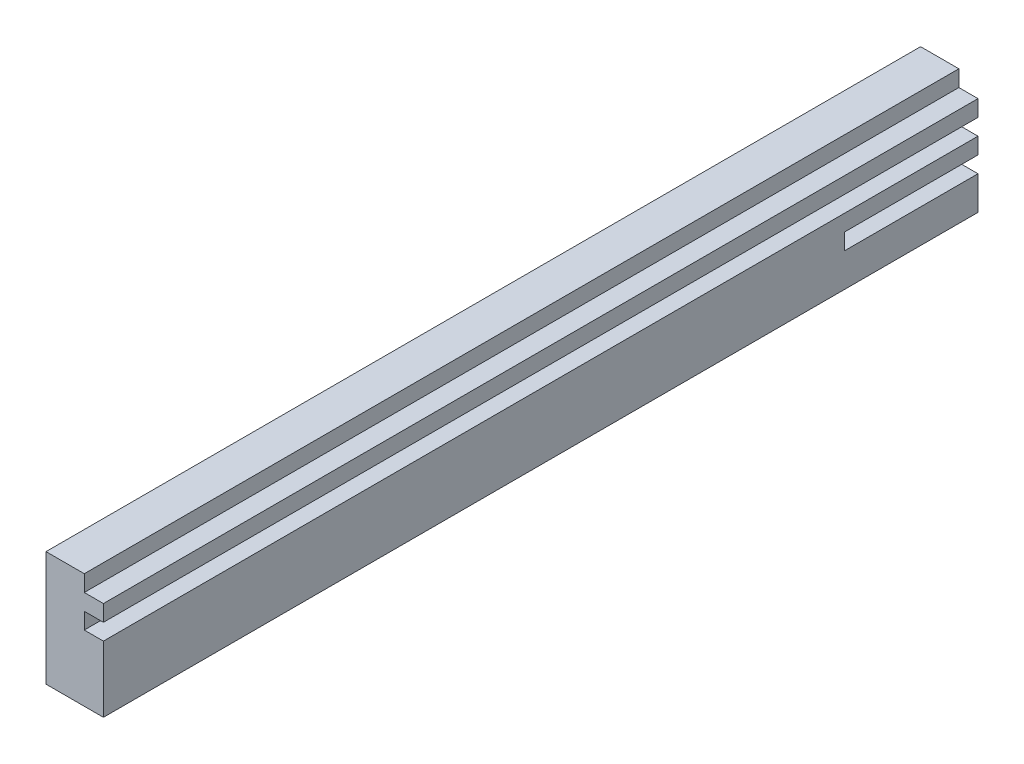
SolidWorks part; units mm, degrees
ref_plane "Front Plane" through (0, 0, 0) normal (0, 0, 1) x (1, 0, 0)
ref_plane "Top Plane" through (0, 0, 0) normal (0, 1, 0) x (1, 0, 0)
ref_plane "Right Plane" through (0, 0, 0) normal (1, 0, 0) x (0, 0, -1)
sketch "Sketch1" plane through (0, 0, 0) normal (1, 0, 0) x (0, 0, -1)
  line L1 (0, 0) -> (457, 0)
  line L2 (0, 0) -> (0, 60)
  line L3 (0, 60) -> (457, 60)
  line L4 (457, 0) -> (457, 60)
  dimension "D1" = 60
  dimension "D2" = 457
extrude "Boss-Extrude1" add sketch "Sketch1" along normal blind 30
sketch "Sketch2" plane through (30, 0, 0) normal (1, 0, 0) x (0, 0, -1)
  line L0 (457, 0) -> (457, 60) construction
  line L1 (0, 60) -> (457, 60)
  line L2 (0, 60) -> (0, 51.5)
  line L3 (0, 51.5) -> (457, 51.5)
  line L4 (457, 60) -> (457, 51.5)
  line L5 (0, 60) -> (0, 0) construction
  line L6 (0, 43) -> (457, 43)
  line L7 (0, 43) -> (0, 34.5)
  line L8 (0, 34.5) -> (457, 34.5)
  line L9 (457, 43) -> (457, 34.5)
  line L11 (457, 26) -> (387.1115, 26)
  line L12 (457, 26) -> (457, 17.5)
  line L13 (457, 17.5) -> (387.1115, 17.5)
  line L14 (387.1115, 26) -> (387.1115, 17.5)
  dimension "D1" = 8.5
  dimension "D2" = 8.5
  dimension "D3" = 8.5
  dimension "D4" = 8.5
  dimension "D5" = 8.5
extrude "Cut-Extrude1" cut sketch "Sketch2" against normal blind 10 contours L2 L1 L4 L3 | L7 L6 L9 L8 | L12 L11 L14 L13
